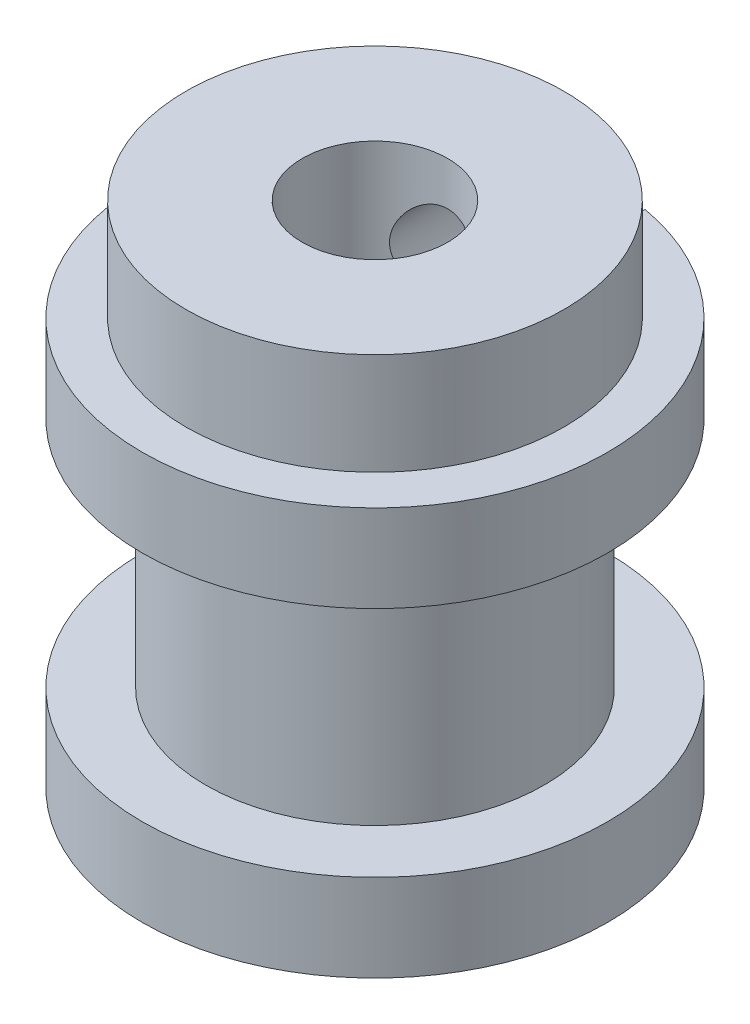
SolidWorks part; units mm, degrees
material "PUR"
ref_plane "Plan de face" through (0, 0, 0) normal (0, 0, 1) x (1, 0, 0)
ref_plane "Plan de dessus" through (0, 0, 0) normal (0, 1, 0) x (1, 0, 0)
ref_plane "Plan de droite" through (0, 0, 0) normal (1, 0, 0) x (0, 0, -1)
sketch "Esquisse1" plane through (0, 0, 0) normal (0, 0, 1) x (1, 0, 0)
  line L0 (0, 5.9193) -> (0, -5.4162) construction
  line L1 (2.5, -7) -> (2.5, 10.5)
  line L2 (2.5, 10.5) -> (6.5, 10.5)
  line L3 (6.5, 10.5) -> (6.5, 7)
  line L4 (6.5, 7) -> (8, 7)
  line L5 (8, 7) -> (8, 4)
  line L6 (8, 4) -> (5.82, 4)
  line L7 (5.82, 4) -> (5.82, -4)
  line L8 (5.82, -4) -> (8, -4)
  line L9 (8, -4) -> (8, -7)
  line L10 (8, -7) -> (2.5, -7)
  line L11 (0, 0) -> (14.9645, 0) construction
  dimension "D1" = 16
  dimension "D2" = 11.64
  dimension "D3" = 14
  dimension "D4" = 17.5
  dimension "D5" = 8
  dimension "D6" = 5
  dimension "D7" = 13
revolve "Révolution1" add sketch "Esquisse1" angle 360 about L0
sketch "Esquisse2" plane through (0, 0, 0) normal (0, 0, 1) x (1, 0, 0)
  line L0 (2.5, 10.5) -> (-2.5, 10.5) construction
  circle A0 centre (0, 7.5) radius 1.5
  dimension "D1" = 3
  dimension "D2" = 3
extrude "Enlèv. mat.-Extru.1" cut sketch "Esquisse2" against normal through all
